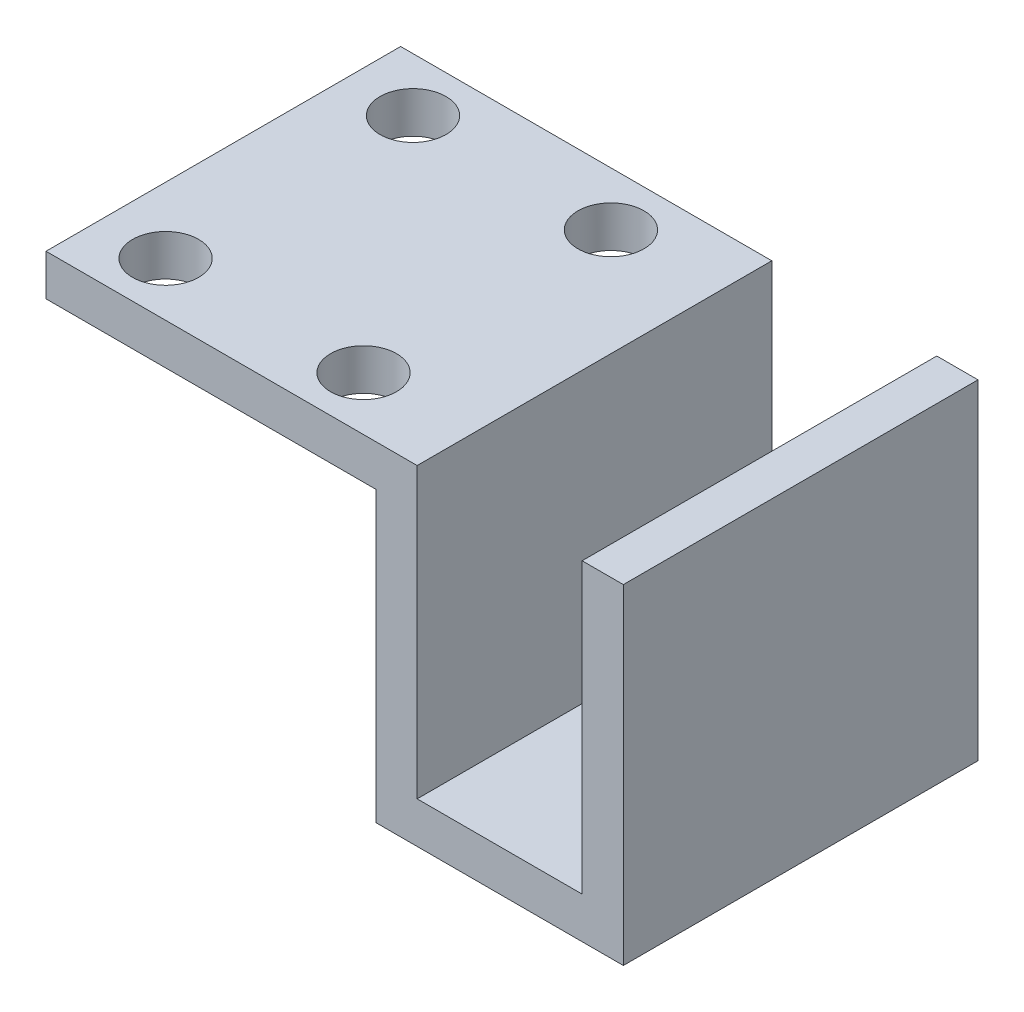
SolidWorks part; units mm, degrees
ref_plane "前视基准面" through (0, 0, 0) normal (0, 0, 1) x (1, 0, 0)
ref_plane "上视基准面" through (0, 0, 0) normal (0, 1, 0) x (1, 0, 0)
ref_plane "右视基准面" through (0, 0, 0) normal (1, 0, 0) x (0, 0, -1)
sketch "Sketch1" plane through (0, 0, 0) normal (0, 0, 1) x (1, 0, 0)
  line L0 (0, 0) -> (40, 0)
  line L1 (0, 0) -> (0, 5)
  line L2 (0, 5) -> (45, 5)
  line L3 (45, 5) -> (45, -30)
  line L4 (45, -30) -> (65, -30)
  line L5 (40, 0) -> (40, -35)
  line L6 (40, -35) -> (70, -35)
  line L7 (65, -30) -> (65, 5)
  line L8 (65, 5) -> (70, 5)
  line L9 (70, 5) -> (70, -35)
extrude "Boss-Extrude1" add sketch "Sketch1" along normal blind 43
sketch "Sketch2" plane through (0, 0, 0) normal (0, -1, 0) x (1, 0, 0)
  line L0 (0, 43) -> (0, 0) construction
  line L1 (0, 21.5) -> (0, 36.5) construction
  line L2 (40, 43) -> (40, 0) construction
  line L3 (0, 36.5) -> (40, 36.5) construction
  line L4 (0, 36.5) -> (8, 36.5) construction
  line L5 (40, 36.5) -> (32, 36.5) construction
  line L6 (0, 21.5) -> (50000, 21.5) construction
  circle A0 centre (8, 36.5) radius 4
  circle A1 centre (32, 36.5) radius 4
  circle A2 centre (32, 6.5) radius 4
  circle A3 centre (8, 6.5) radius 4
  point P0 (0, 21.5)
  point P5 (40, 36.5)
  point P6 (20, 36.5)
  point P17 (40, 21.5)
extrude "Cut-Extrude2" cut sketch "Sketch2" against normal blind 10
